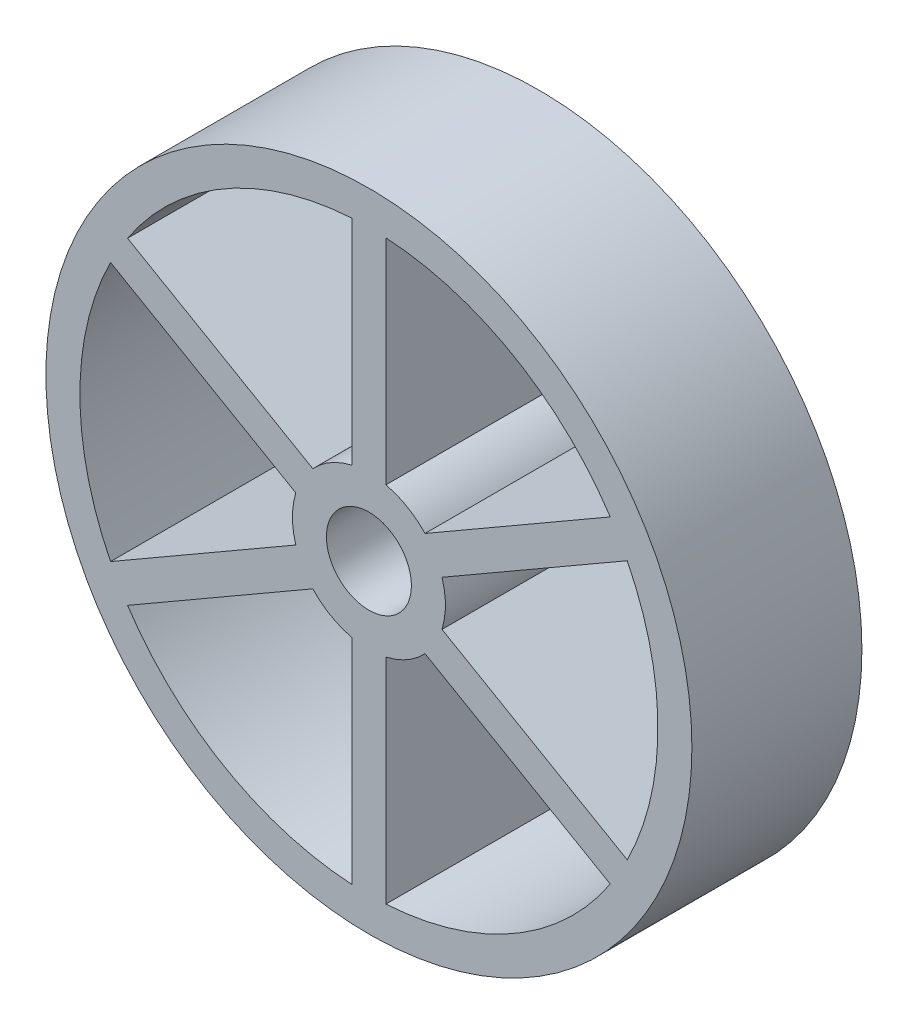
SolidWorks part; units mm, degrees
ref_plane "Front Plane" through (0, 0, 0) normal (0, 0, 1) x (1, 0, 0)
ref_plane "Top Plane" through (0, 0, 0) normal (0, 1, 0) x (1, 0, 0)
ref_plane "Right Plane" through (0, 0, 0) normal (1, 0, 0) x (0, 0, -1)
sketch "Sketch1" plane through (0, 0, 0) normal (0, 0, 1) x (1, 0, 0)
  circle A0 centre (0, 0) radius 19
  dimension "D1" = 38
extrude "Boss-Extrude1" add sketch "Sketch1" along normal blind 10
sketch "Sketch2" plane through (0, 0, 10) normal (0, 0, 1) x (1, 0, 0)
  circle A0 centre (0, 0) radius 2.5
  dimension "D1" = 5
extrude "Cut-Extrude1" cut sketch "Sketch2" against normal blind 10
sketch "Sketch3" plane through (0, 0, 10) normal (0, 0, 1) x (1, 0, 0)
  line L0 (0, 0) -> (0, 17) construction
  line L1 (-1, 4.3875) -> (-1, 16.9706)
  line L2 (1, 4.3875) -> (1, 16.9706)
  line L3 (3.2997, 3.0598) -> (14.1969, 9.3513)
  line L4 (4.2997, 1.3277) -> (15.1969, 7.6193)
  line L5 (4.2997, -1.3277) -> (15.1969, -7.6193)
  line L6 (3.2997, -3.0598) -> (14.1969, -9.3513)
  line L7 (1, -4.3875) -> (1, -16.9706)
  line L8 (-1, -4.3875) -> (-1, -16.9706)
  line L9 (-3.2997, -3.0598) -> (-14.1969, -9.3513)
  line L10 (-4.2997, -1.3277) -> (-15.1969, -7.6193)
  line L11 (-4.2997, 1.3277) -> (-15.1969, 7.6193)
  line L12 (-3.2997, 3.0598) -> (-14.1969, 9.3513)
  circle A0 centre (0, 0) radius 4.5
  circle A1 centre (0, 0) radius 17
  circle A2 centre (0, 0) radius 19 construction
  circle A3 centre (0, 0) radius 2.5 construction
  dimension "D1" = 2
  dimension "D2" = 2
  dimension "D3" = 2
  dimension "D4" = 6
extrude "Cut-Extrude2" cut sketch "Sketch3" against normal blind 10 contours L1 A1 L12 A0 | L11 A1 L10 A0 | L9 A1 L8 A0 | L7 A1 L6 A0 | L5 A1 L4 A0 | L3 A1 L2 A0
